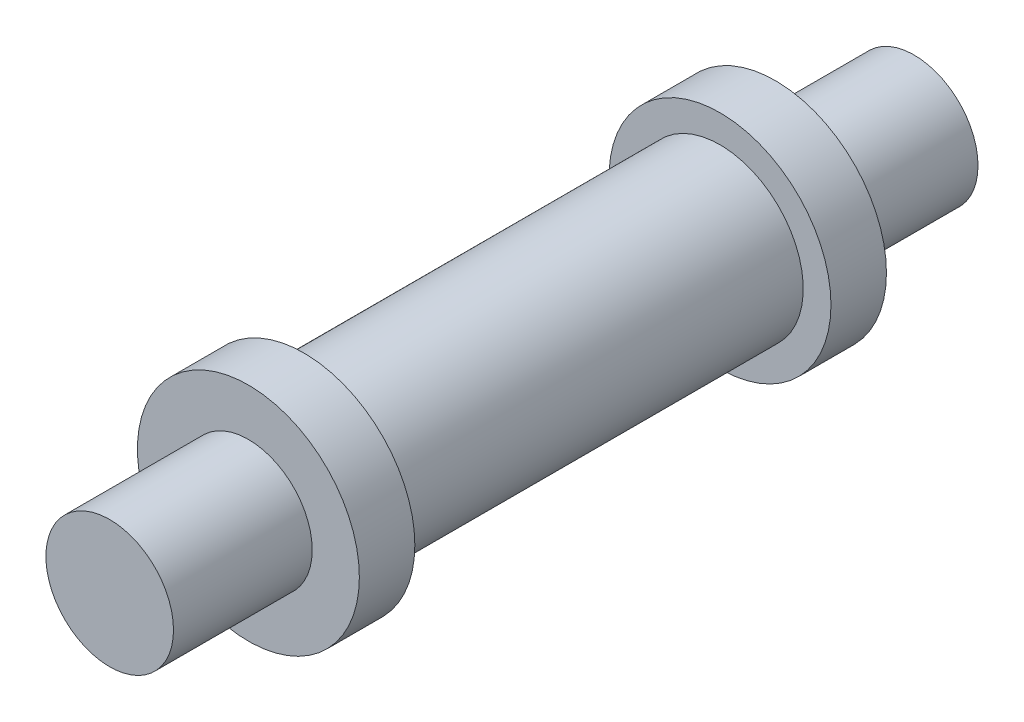
SolidWorks part; units mm, degrees
ref_plane "Front Plane" through (0, 0, 0) normal (0, 0, 1) x (1, 0, 0)
ref_plane "Top Plane" through (0, 0, 0) normal (0, 1, 0) x (1, 0, 0)
ref_plane "Right Plane" through (0, 0, 0) normal (1, 0, 0) x (0, 0, -1)
sketch "Sketch1" plane through (0, 0, 0) normal (0, 0, 1) x (1, 0, 0)
  circle A0 centre (0, 0) radius 2.921
  dimension "D1" = 5.842
extrude "Boss-Extrude1" add sketch "Sketch1" along normal blind 6.35
sketch "Sketch2" plane through (0, 0, 6.35) normal (0, 0, 1) x (1, 0, 0)
  circle A0 centre (0, 0) radius 5.08
  dimension "D1" = 10.16
extrude "Boss-Extrude2" add sketch "Sketch2" along normal blind 2.54
sketch "Sketch3" plane through (0, 0, 8.89) normal (0, 0, 1) x (1, 0, 0)
  circle A0 centre (0, 0) radius 3.81
  dimension "D1" = 7.62
extrude "Boss-Extrude3" add sketch "Sketch3" along normal blind 19.05
sketch "Sketch4" plane through (0, 0, 27.94) normal (0, 0, 1) x (1, 0, 0)
  circle A0 centre (0, 0) radius 5.08
extrude "Boss-Extrude4" add sketch "Sketch4" along normal blind 2.54
sketch "Sketch5" plane through (0, 0, 30.48) normal (0, 0, 1) x (1, 0, 0)
  circle A0 centre (0, 0) radius 2.921
  dimension "D1" = 5.842
extrude "Boss-Extrude5" add sketch "Sketch5" along normal blind 6.35
